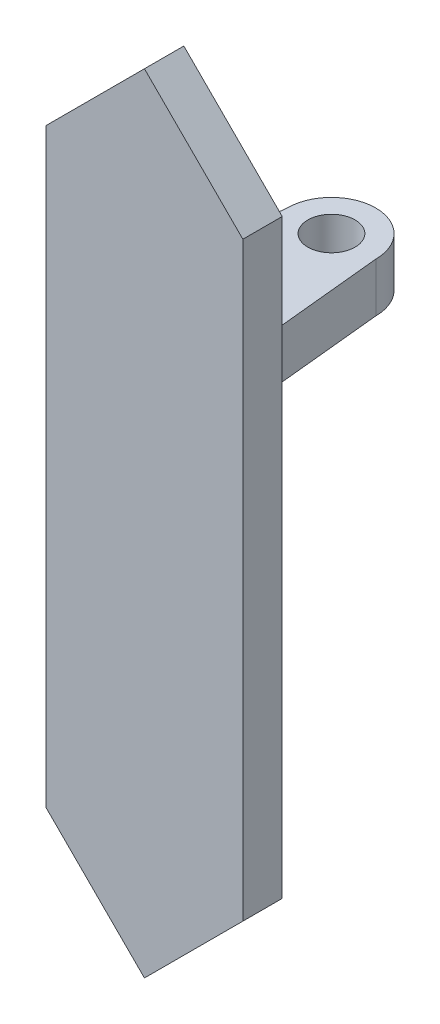
SolidWorks part; units mm, degrees
ref_plane "前视基准面" through (0, 0, 0) normal (0, 0, 1) x (1, 0, 0)
ref_plane "上视基准面" through (0, 0, 0) normal (0, 1, 0) x (1, 0, 0)
ref_plane "右视基准面" through (0, 0, 0) normal (1, 0, 0) x (0, 0, -1)
sketch "草图1" plane through (0, 0, 0) normal (0, 0, 1) x (1, 0, 0)
  line L2 (0.1473, 10) -> (0.1473, 70)
  line L4 (20.1473, 10) -> (20.1473, 70)
  line L5 (0.1473, 70) -> (10.1473, 80)
  line L6 (10.1473, 80) -> (20.1473, 70)
  line L8 (10.1473, 0) -> (20.1473, 10)
  line L9 (0.1473, 10) -> (10.1473, 0)
extrude "凸台-拉伸1" add sketch "草图1" along normal blind 4 contours L2 L9 L8 L4 L6 L5
sketch "草图2" plane through (0, 0, 0) normal (0, 0, -1) x (-1, 0, 0)
  line L0 (-10.1473, 56) -> (-10.1473, 80)
  line L5 (-16.1473, 56) -> (-4.1473, 56)
  line L6 (-16.1473, 56) -> (-16.1473, 51)
  line L7 (-16.1473, 51) -> (-4.1473, 51)
  line L8 (-4.1473, 56) -> (-4.1473, 51)
  line L9 (-16.1473, 56) -> (-4.1473, 51) construction
  line L10 (-16.1473, 51) -> (-4.1473, 56) construction
  point P8 (-10.1473, 53.5)
  dimension "D1" = 24
extrude "凸台-拉伸2" add sketch "草图2" along normal blind 20 contours L8 L5 L6 L7
sketch "草图6" plane through (0, 51, 0) normal (0, -1, 0) x (1, 0, 0)
  line L3 (5.6473, -15) -> (4.1473, 0)
  line L4 (14.6473, -15) -> (16.1473, 0)
  circle A0 centre (10.1473, -15) radius 4.5
  circle A1 centre (10.1473, -15) radius 2.4
  line M5 (4.1473, 0) -> (4.1473, -20)
  line M6 (4.1473, -20) -> (16.1473, -20)
  line M7 (16.1473, -20) -> (16.1473, 0)
extrude "切除-拉伸5" cut sketch "草图6" against normal blind 21 contours A1 | A0 L3 L4 M5 M6 M7
